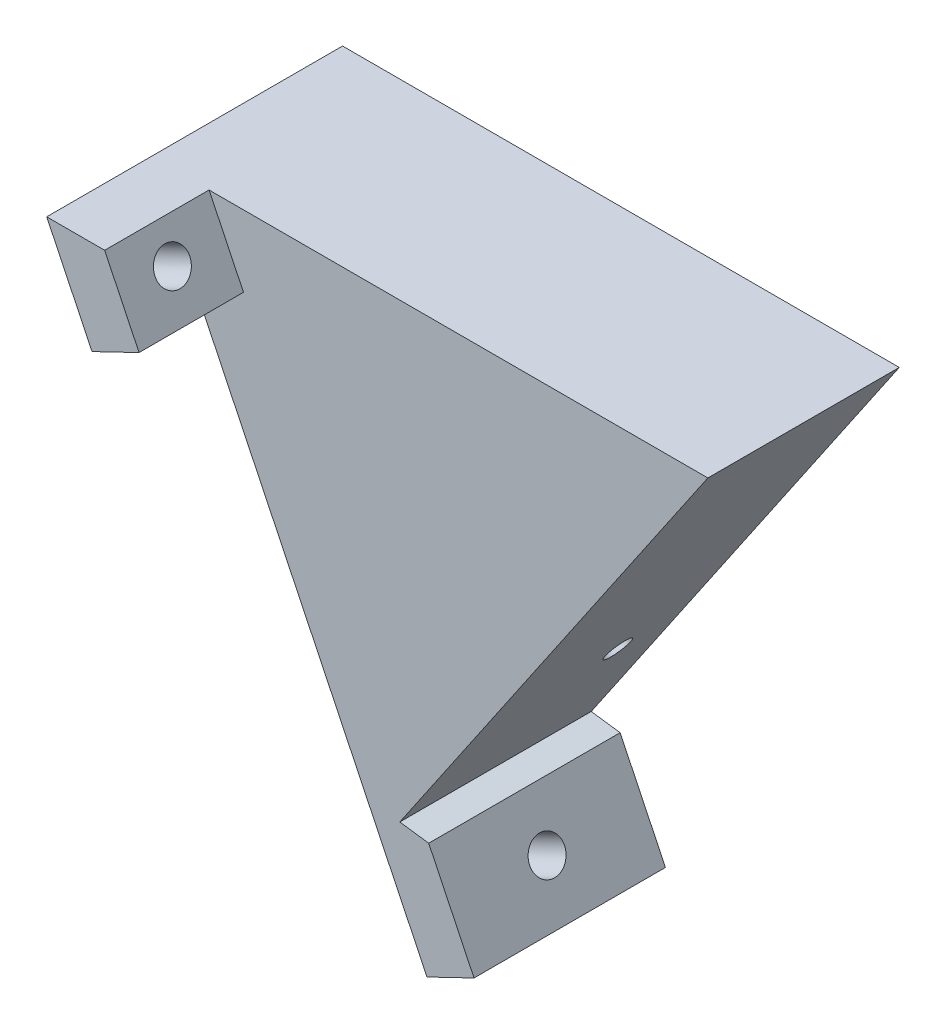
SolidWorks part; units mm, degrees
material "ABS"
ref_plane "Front Plane" through (0, 0, 0) normal (0, 0, 1) x (1, 0, 0)
ref_plane "Top Plane" through (0, 0, 0) normal (0, 1, 0) x (1, 0, 0)
ref_plane "Right Plane" through (0, 0, 0) normal (1, 0, 0) x (0, 0, -1)
sketch "Sketch1" plane through (0, 0, 0) normal (0, 0, 1) x (1, 0, 0)
  line L0 (-36.2386, 24.2413) -> (-9.7428, -30.7587)
  line L1 (-9.7428, -30.7587) -> (27.7446, 24.2413)
  line L2 (27.7446, 24.2413) -> (-36.2386, 24.2413)
  dimension "D1" = 55
  dimension "D2" = 55
  dimension "D3" = 60
extrude "Boss-Extrude1" add sketch "Sketch1" along normal blind 22
sketch "Sketch6" plane through (-19.9343, -9.6032, 0) normal (-0.9009, -0.434, 0) x (0, 0, 1)
  line L0 (22, 37.5671) -> (22, -23.4823) construction
  line L1 (34, 37.5671) -> (22, 37.5671)
  line L2 (34, 37.5671) -> (34, 25.5671)
  line L3 (34, 25.5671) -> (22, 25.5671)
  line L4 (22, 37.5671) -> (22, 25.5671)
  line L5 (0, -23.4823) -> (22, -23.4823)
  line L6 (0, -23.4823) -> (0, -35.4823)
  line L7 (0, -35.4823) -> (22, -35.4823)
  line L8 (22, -23.4823) -> (22, -35.4823)
  line L9 (22, 37.5671) -> (0, 37.5671) construction
  dimension "D1" = 12
  dimension "D2" = 12
  dimension "D3" = 0
  dimension "D4" = 12
  dimension "D5" = 0
  dimension "D6" = 0
extrude "Boss-Extrude4" add sketch "Sketch6" against normal blind 6
sketch "Sketch8" plane through (0, 0, 0) normal (0, 0, -1) x (-1, 0, 0)
  line L0 (9.7428, -30.7587) -> (4.3373, -28.1546)
  line L1 (4.3373, -28.1546) -> (7.6613, -27.7048)
  line L2 (9.7428, -30.7587) -> (-27.7446, 24.2413) construction
  line L3 (7.6613, -27.7048) -> (9.7428, -30.7587)
extrude "Boss-Extrude5" add sketch "Sketch8" against normal up to vertex (22 mm away) up to point (27.7446, 24.2413, 22)
sketch "Sketch9" plane through (-14.5288, -6.9992, 0) normal (0.9009, 0.434, 0) x (0, 0, -1)
  line L2 (-22, 25.5671) -> (-34, 25.5671) construction
  line L3 (0, -35.4823) -> (-22, -35.4823) construction
  line L4 (-22, -35.4823) -> (-22, -23.4823) construction
  circle A0 centre (-28, 30.5671) radius 2
  circle A1 centre (-11, -29.4823) radius 2
  point P9 (-28, 25.5671)
  point P12 (-11, -35.4823)
  point P15 (-22, -29.4823)
  dimension "D1" = 4
  dimension "D2" = 4
  dimension "D3" = 5
  dimension "D4" = 0
  dimension "D5" = 0
  dimension "D6" = 0
extrude "Cut-Extrude9" cut sketch "Sketch9" against normal blind 6
sketch "Sketch10" plane through (7.6623, -5.2226, 0) normal (0.8263, -0.5632, 0) x (0, 0, -1)
  line L0 (-22, 35.657) -> (0, 35.657) construction
  line L1 (0, -27.2079) -> (0, 35.657) construction
  circle A0 centre (-7, -9.343) radius 1.5
  dimension "D1" = 3
  dimension "D3" = 7
  dimension "D2" = 45
extrude "Cut-Extrude10" cut sketch "Sketch10" against normal blind 36
sketch "Sketch12" plane through (0, 0, 22) normal (0, 0, -1) x (-1, 0, 0)
  line L0 (30.8332, 26.8454) -> (29.5787, 24.2413)
  line L1 (29.5787, 24.2413) -> (36.2386, 24.2413)
  line L2 (36.2386, 24.2413) -> (30.8332, 26.8454)
extrude "Cut-Extrude11" cut sketch "Sketch12" against normal blind 20
